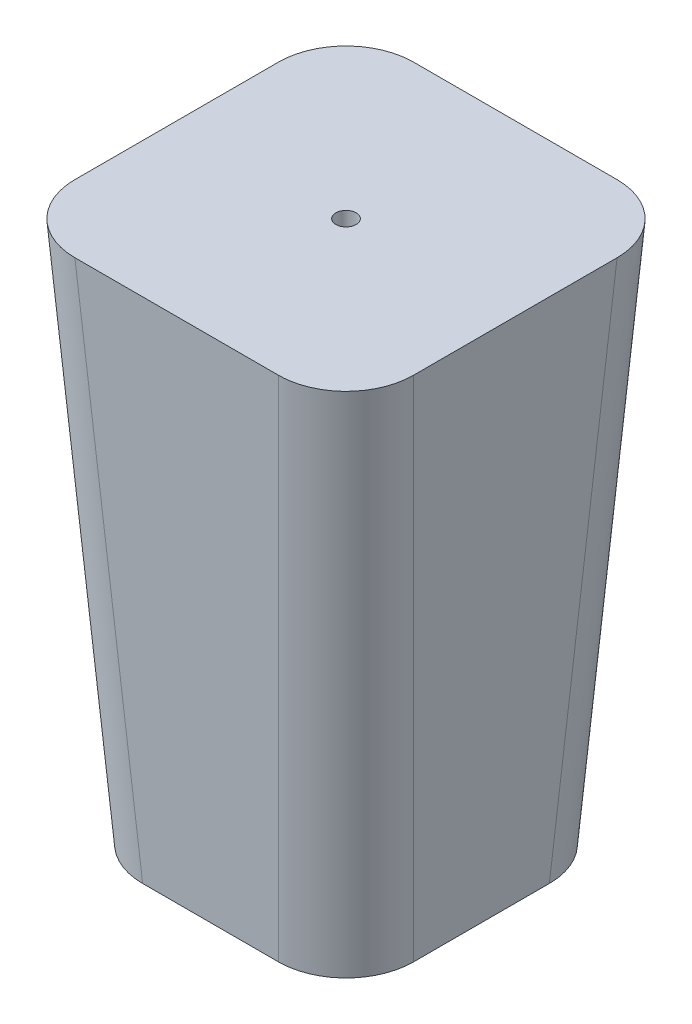
SolidWorks part; units mm, degrees
ref_plane "Front Plane" through (0, 0, 0) normal (0, 0, 1) x (1, 0, 0)
ref_plane "Top Plane" through (0, 0, 0) normal (0, 1, 0) x (1, 0, 0)
ref_plane "Right Plane" through (0, 0, 0) normal (1, 0, 0) x (0, 0, -1)
sketch "Sketch1" plane through (0, 0, 0) normal (0, 1, 0) x (1, 0, 0)
  line L1 (-20, -20) -> (20, -20)
  line L2 (-20, -20) -> (-20, 20)
  line L3 (-20, 20) -> (20, 20)
  line L4 (20, -20) -> (20, 20)
  line L5 (-20, -20) -> (20, 20) construction
  line L6 (-20, 20) -> (20, -20) construction
  point P0 (0, 0)
  dimension "D1" = 40
ref_plane "Plane1" through (0, 80, 0) normal (0, 1, 0) x (1, 0, 0)
sketch "Sketch2" plane through (0, 80, 0) normal (0, 1, 0) x (1, 0, 0)
  line L1 (-25, -25) -> (25, -25)
  line L2 (-25, -25) -> (-25, 25)
  line L3 (-25, 25) -> (25, 25)
  line L4 (25, -25) -> (25, 25)
  line L5 (-25, -25) -> (25, 25) construction
  line L6 (-25, 25) -> (25, -25) construction
  point P0 (0, 0)
  dimension "D1" = 50
loft "Loft1" add profiles "Sketch2", "Sketch1"
sketch "Sketch3" plane through (0, 80, 0) normal (0, 1, 0) x (1, 0, 0)
  circle A0 centre (0, 0) radius 1.5
  dimension "D1" = 3
extrude "Cut-Extrude1" cut sketch "Sketch3" against normal blind 3
ref_plane "Plane2" through (0, 40, 0) normal (0, 1, 0) x (1, 0, 0)
mirror "Mirror1" about plane through (0, 40, 0) normal (0, 1, 0) of "Cut-Extrude1"
fillet "Fillet1" radius 10 4 edges
